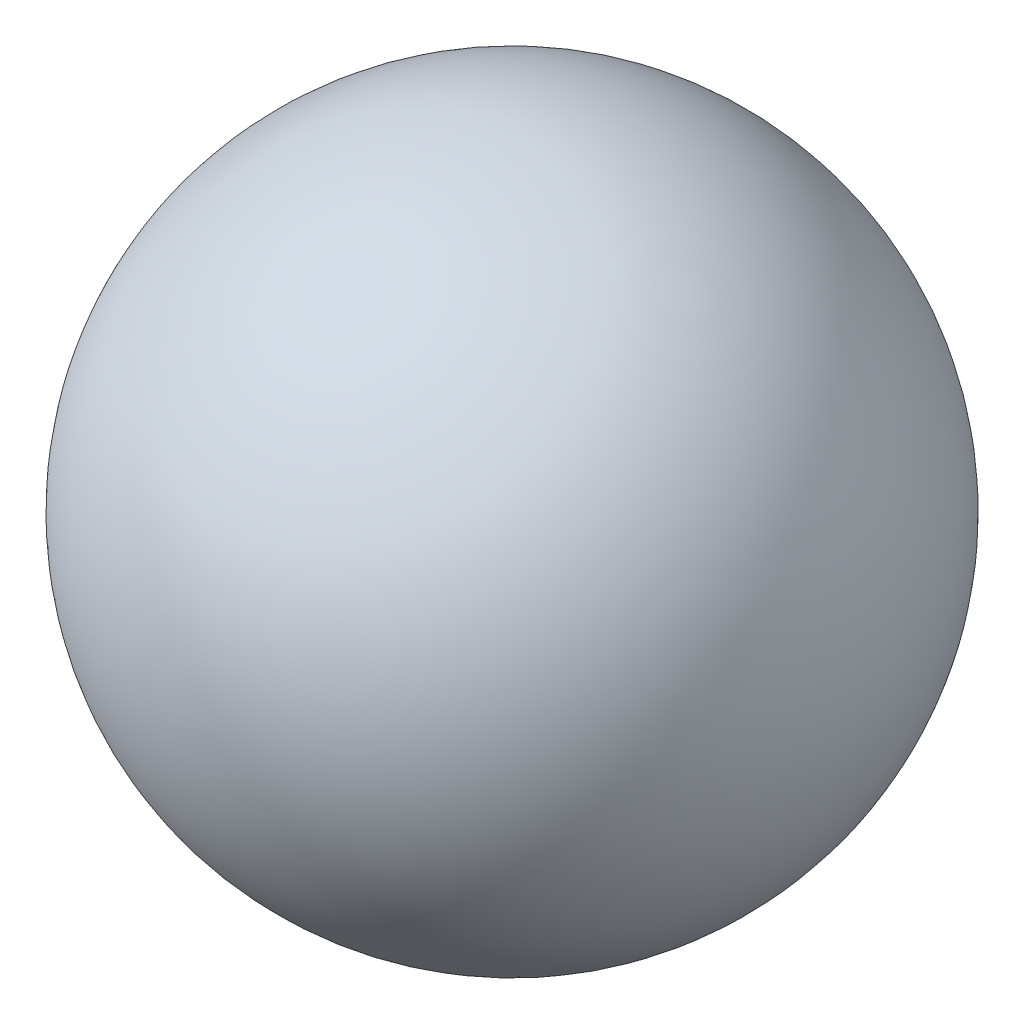
SolidWorks part; units mm, degrees
ref_plane "Front Plane" through (0, 0, 0) normal (0, 0, 1) x (1, 0, 0)
ref_plane "Top Plane" through (0, 0, 0) normal (0, 1, 0) x (1, 0, 0)
ref_plane "Right Plane" through (0, 0, 0) normal (1, 0, 0) x (0, 0, -1)
sketch "Sketch1" plane through (0, 0, 0) normal (0, 0, 1) x (1, 0, 0)
  line L0 (-2.5908, 0.1778) -> (2.5908, 0.1778)
  line L1 (-2.5908, 0.1778) -> (2.5908, 0.1778) construction
  arc A0 (2.5908, 0.1778) -> (-2.5908, 0.1778) centre (0, 0.1778) ccw
revolve "Revolve1" add sketch "Sketch1" angle 360 about L1
